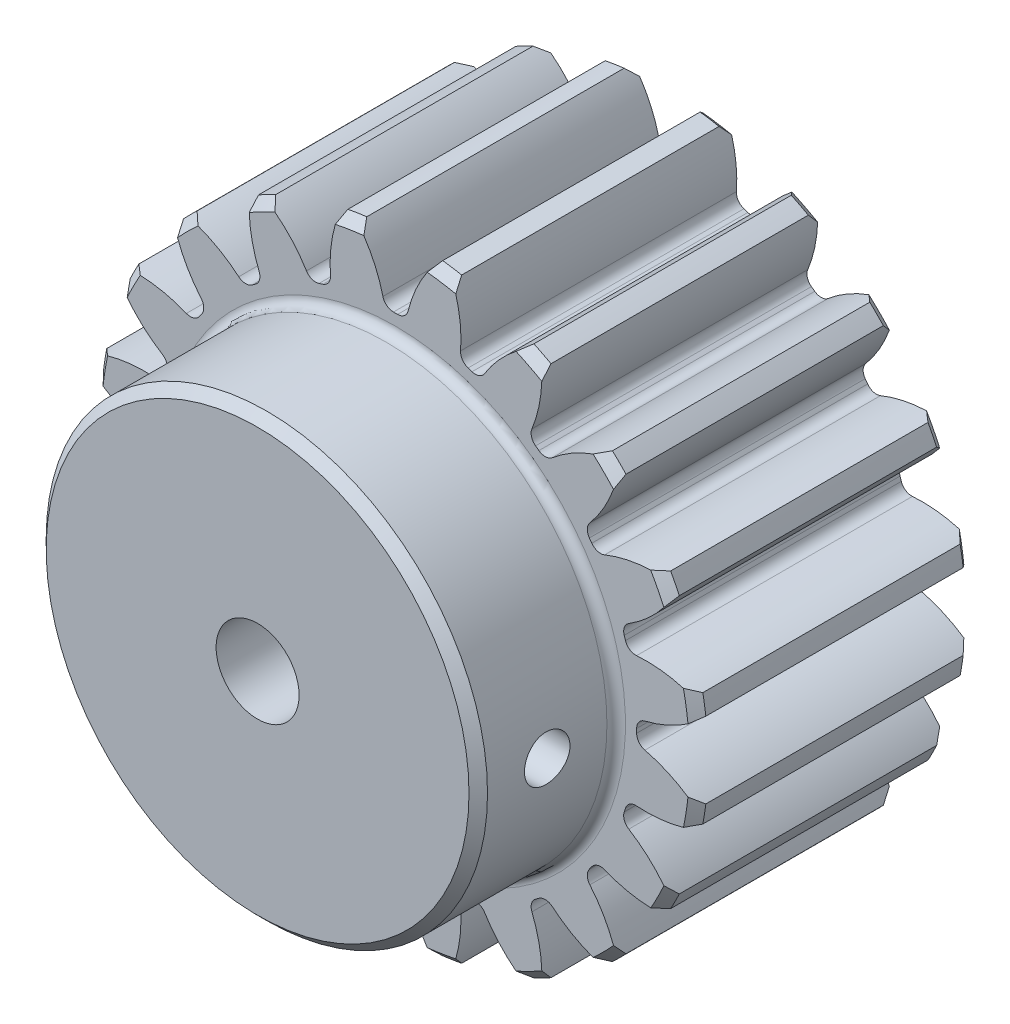
SolidWorks part; units mm, degrees
ref_plane "Front Plane" through (0, 0, 0) normal (0, 0, 1) x (1, 0, 0)
ref_plane "Top Plane" through (0, 0, 0) normal (0, 1, 0) x (1, 0, 0)
ref_plane "Right Plane" through (0, 0, 0) normal (1, 0, 0) x (0, 0, -1)
sketch "Sketch1" plane through (0, 0, 0) normal (0, 0, 1) x (1, 0, 0)
  line L0 (0, 0) -> (0, 20) construction
  line L1 (-6.4279, 22.3396) -> (6.4279, 17.6604) construction
  circle A0 centre (0, 0) radius 17.5 construction
  circle A1 centre (0, 0) radius 22 construction
  circle A2 centre (0, 0) radius 20 construction
  circle A3 centre (0, 0) radius 18.7939 construction
  circle A4 centre (0, 0) radius 16 construction
  circle A5 centre (0, 0) radius 6 construction
  point P8 (1, 0)
  point P13 (10, 0)
  dimension "OD" = 44
  dimension "Root Diameter" = 35
  dimension "Gear Pitch Diameter" = 40
  dimension "Base Diameter" = 37.5877
  dimension "Hub Diameter" = 32
  dimension "For Shaft Diameter" = 12
  dimension "Pressure Angle" = 20
  dimension "Number of Teeth" = 20
  dimension "Module" = 2
sketch "Sketch2" plane through (0, 0, 0) normal (1, 0, 0) x (0, 0, -1)
  line L0 (-10, 0) -> (20, 0) construction
  line L1 (20, 22) -> (20, -22) construction
  line L2 (0, -16) -> (-10, -16) construction
  line L3 (-10, 22) -> (20, 22) construction
  line L8 (-10, -16) -> (-10, 16) construction
  point P4 (0, 22)
  point P5 (-5, 0)
  dimension "Overall Width" = 30
  dimension "Hub Width" = 10
  dimension "Approx Set Screw Positon" = 5
  dimension "Face Width" = 20
sketch "Sketch3" plane through (0, 0, 0) normal (0, 0, 1) x (1, 0, 0)
  circle A0 centre (0, 0) radius 22
  circle A1 centre (0, 0) radius 22 construction
extrude "Boss-Extrude1" add sketch "Sketch3" against normal up to vertex (20 mm away) and the other way up to vertex (10 mm away) up to point (0, 0, -20) other way up to point (0, 0, 10)
sketch "Sketch5" plane through (0, 0, 0) normal (1, 0, 0) x (0, 0, -1)
  line L1 (0, 16) -> (-10, 16)
  line L2 (0, 16) -> (0, 22)
  line L3 (0, 22) -> (-10, 22)
  line L4 (-10, 16) -> (-10, 22)
  line L5 (-10, 0) -> (20, 0)
  line L6 (-10, 0) -> (-10, 6)
  line L7 (-10, 6) -> (20, 6)
  line L8 (20, 0) -> (20, 6)
  point P5 (0, 16)
  point P12 (0, 6)
revolve "Cut-Revolve1" cut sketch "Sketch5" angle 360 about L0
fillet "Fillet2" radius 0.671 1 edges at (0, -16, 0)
chamfer "Chamfer1" distance 0.671 angle 45 5 edges at (0, -6, -20) (0, -22, 0) (22, 0, -20) (0, -6, 10) (0, -16, 10)
sketch "Sketch4" plane through (0, 0, 0) normal (0, 0, 1) x (1, 0, 0)
  line L0 (17.4824, 0.7854) -> (17.4824, -0.7854)
  arc A3 (21.827, 2.7536) -> (21.827, -2.7536) centre (0, 0) cw
  circle A4 centre (0, 0) radius 22 construction
  arc A5 (17.4824, 0.7854) -> (21.827, 2.7536) centre (15.7482, 10.3925) ccw
  circle A8 centre (0, 0) radius 17.5 construction
  arc A9 (17.4824, -0.7854) -> (21.827, -2.7536) centre (15.7482, -10.3925) cw
  spline S0 degree 4 poles (18.7558, 1.1951) (18.7609, 1.1955) (18.7753, 1.1968) (18.8024, 1.2001) (18.8466, 1.2066) (18.9026, 1.2166) (18.9748, 1.2314) (19.0595, 1.2513) (19.1523, 1.2758) (19.2527, 1.3052) (19.3525, 1.337) (19.4517, 1.371) (19.55, 1.4069) (19.6686, 1.4528) (19.8101, 1.5113) (19.9744, 1.5844) (20.1594, 1.6731) (20.3463, 1.7697) (20.5289, 1.8696) (20.7118, 1.9763) (20.8875, 2.0836) (21.0683, 2.2008) (21.2342, 2.312) (21.4181, 2.4428) (21.5658, 2.5503) (21.7584, 2.6988) (21.8714, 2.7885) (22.0028, 2.8958) (22.0607, 2.9446) (22.0964, 2.9747) knots 0 0 0 0 0 0.005377 0.015084 0.028532 0.04661 0.064855 0.092111 0.119476 0.146842 0.174209 0.201575 0.228941 0.256307 0.307035 0.361767 0.4165 0.471232 0.525964 0.580697 0.635429 0.690161 0.744894 0.799626 0.854358 0.909091 0.954545 1 1 1 1 1 construction
  spline S1 degree 4 poles (18.7558, 1.1951) (18.7609, 1.1955) (18.7753, 1.1968) (18.8024, 1.2001) (18.8466, 1.2066) (18.9026, 1.2166) (18.9748, 1.2314) (19.0595, 1.2513) (19.1523, 1.2758) (19.2527, 1.3052) (19.3525, 1.337) (19.4517, 1.371) (19.55, 1.4069) (19.6686, 1.4528) (19.8101, 1.5113) (19.9744, 1.5844) (20.1594, 1.6731) (20.3463, 1.7697) (20.5289, 1.8696) (20.7118, 1.9763) (20.8875, 2.0836) (21.0683, 2.2008) (21.2342, 2.312) (21.4181, 2.4428) (21.5658, 2.5503) (21.7166, 2.6666) (21.7897, 2.724) (21.827, 2.7536) knots 0 0 0 0 0 0.005377 0.015084 0.028532 0.04661 0.064855 0.092111 0.119476 0.146842 0.174209 0.201575 0.228941 0.256307 0.307035 0.361767 0.4165 0.471232 0.525964 0.580697 0.635429 0.690161 0.744894 0.799626 0.854358 0.909091 0.909091 0.909091 0.909091 0.909091 construction
  spline S2 degree 4 poles (18.7558, -1.1951) (18.7609, -1.1955) (18.7753, -1.1968) (18.8024, -1.2001) (18.8466, -1.2066) (18.9026, -1.2166) (18.9748, -1.2314) (19.0595, -1.2513) (19.1523, -1.2758) (19.2527, -1.3052) (19.3525, -1.337) (19.4517, -1.371) (19.55, -1.4069) (19.6686, -1.4528) (19.8101, -1.5113) (19.9744, -1.5844) (20.1594, -1.6731) (20.3463, -1.7697) (20.5289, -1.8696) (20.7118, -1.9763) (20.8875, -2.0836) (21.0683, -2.2008) (21.2342, -2.312) (21.4181, -2.4428) (21.5658, -2.5503) (21.7584, -2.6988) (21.8714, -2.7885) (22.0028, -2.8958) (22.0607, -2.9446) (22.0964, -2.9747) knots 0 0 0 0 0 0.005377 0.015084 0.028532 0.04661 0.064855 0.092111 0.119476 0.146842 0.174209 0.201575 0.228941 0.256307 0.307035 0.361767 0.4165 0.471232 0.525964 0.580697 0.635429 0.690161 0.744894 0.799626 0.854358 0.909091 0.954545 1 1 1 1 1 construction
  spline S3 degree 4 poles (18.7558, -1.1951) (18.7609, -1.1955) (18.7753, -1.1968) (18.8024, -1.2001) (18.8466, -1.2066) (18.9026, -1.2166) (18.9748, -1.2314) (19.0595, -1.2513) (19.1523, -1.2758) (19.2527, -1.3052) (19.3525, -1.337) (19.4517, -1.371) (19.55, -1.4069) (19.6686, -1.4528) (19.8101, -1.5113) (19.9744, -1.5844) (20.1594, -1.6731) (20.3463, -1.7697) (20.5289, -1.8696) (20.7118, -1.9763) (20.8875, -2.0836) (21.0683, -2.2008) (21.2342, -2.312) (21.4181, -2.4428) (21.5658, -2.5503) (21.7166, -2.6666) (21.7897, -2.724) (21.827, -2.7536) knots 0 0 0 0 0 0.005377 0.015084 0.028532 0.04661 0.064855 0.092111 0.119476 0.146842 0.174209 0.201575 0.228941 0.256307 0.307035 0.361767 0.4165 0.471232 0.525964 0.580697 0.635429 0.690161 0.744894 0.799626 0.854358 0.909091 0.909091 0.909091 0.909091 0.909091 construction
  dimension "D1" = 1.5708
extrude "Cut-Extrude1" cut sketch "Sketch4" against normal through all both and the other way through all
fillet "Fillet1" radius 0.7854 2 edges at (17.4824, 0.7854, -10) (17.4824, -0.7854, -10)
pattern_circular "CirPattern1" count 20 over 360 about axis through (0, 0, 0) along (0, 0, 1) of "Cut-Extrude1", "Fillet1"
sketch "Sketch6" plane through (0, 0, 10) normal (0, 0, 1) x (1, 0, 0)
  circle A0 centre (0, 0) radius 6.671
  circle A1 centre (0, 0) radius 3.0075
  circle A2 centre (0, 0) radius 6.671 construction
  circle M2 centre (0, 0) radius 6.671
  dimension "D1" = 6.015
extrude "Boss-Extrude4" add sketch "Sketch6" against normal through all contours A1 M2
sketch "Sketch7" plane through (0, 0, 0) normal (1, 0, 0) x (0, 0, -1)
  line L0 (-10, 0) -> (0, 0) construction
  line L1 (-10, 15.329) -> (-10, -15.329) construction
  line L2 (0, 16.671) -> (0, -16.671) construction
  circle A0 centre (-5, 0) radius 2.8
  circle A1 centre (-5, 0) radius 2.25
  dimension "D1" = 5.6
  dimension "D2" = 4.5
sketch "Sketch8" plane through (0, 0, 0) normal (1, 0, 0) x (0, 0, -1)
  point P0 (-5, 0)
hole_wizard "M4x0.7 Tapped Hole1" positions "Sketch8" profile "Sketch9" tap size "M4x0.7" standard "ANSI Metric"
sketch "Sketch9" plane through (0, 0, 5) normal (0, 1, 0) x (0, 0, 1)
  line L0 (0, 0) -> (0, 21.827)
  line L1 (0, 21.827) -> (1.65, 21.827)
  line L2 (1.65, 21.827) -> (1.65, 0)
  line L5 (1.65, 0) -> (0, 0)
  line L11 (0, -6.35) -> (0, 107.95) construction
  dimension "Thru Tap Drill Dia." = 3.3
  dimension "Thru Tap Drill Depth" = 21.827
cosmetic thread "Hole Thread1" parameters "D2"=4
equation "\"Number of Teeth\"= 20"
equation "\"Module\"= 2"
equation "\"Diametral Pitch\"= 1 / \"Module\""
equation "\"Dedendum\"= 1.25 / \"Diametral Pitch\""
equation "\"Pitch Diameter\"= \"Module\" * \"Number of Teeth\""
equation "\"Root Diameter\"= \"Pitch Diameter\" - ( 2 * \"Dedendum\" )"
equation "\"Root Diameter@Sketch1\"=\"Root Diameter\""
equation "\"OD@Sketch1\" = \"Outside Diameter\""
equation "\"D1@CirPattern1\"=\"Number of Teeth\""
equation "\"Pressure Angle\"=20"
equation "\"Base Diameter\"= \"Pitch Diameter\" * cos ( \"Pressure Angle\" )"
equation "\"Outside Diameter\"= ( \"Number of Teeth\" + 2 ) / \"Diametral Pitch\""
equation "\"Pitch Angle\"= 360deg / \"Number of Teeth\""
equation "\"Alpha\"= sqr ( \"Pitch Diameter\" ^ 2 - \"Base Diameter\" ^ 2 ) / \"Base Diameter\" * 180 / PI - \"Pressure Angle\""
equation "\"Beta\"= ( \"Pitch Angle\" / 4 - \"Alpha\" )"
equation "\"Phi\"= sqr ( ( \"Outside Diameter\" / 2 ) ^ 2 - ( \"Base Diameter\" / 2 ) ^ 2 ) / ( \"Base Diameter\" / 2 )"
equation "\"Addendum\"= 1 / \"Diametral Pitch\""
equation "\"WorkingDepth\"= 2 / \"Diametral Pitch\""
equation "\"WholeDepth\"= 2.25 / \"Diametral Pitch\""
equation "\"Clearance\"= 0.25 / \"Diametral Pitch\""
equation "\"ToothThickness\"= ( pi * 2 ) / \"Diametral Pitch\""
equation "\"CircularPitch\"= pi / \"Diametral Pitch\""
equation "\"Number of Teeth@Sketch1\"=\"Number of Teeth\""
equation "\"Module@Sketch1\"=\"Module\""
equation "\"Pressure Angle@Sketch1\"=\"Pressure Angle\""
equation "\"Gear Pitch Diameter@Sketch1\"=\"Pitch Diameter\""
equation "\"Base Diameter@Sketch1\"=\"Base Diameter\""
equation "\"Fillet\"= \"Clearance\" * cos ( \"Pressure Angle\" ) * tan ( ( 90 + \"Pressure Angle\" ) / 2 )"
equation "\"D1@Fillet2\"=\"Fillet\""
equation "\"Approx Set Screw Positon@Sketch2\" = \"Hub Width@Sketch2\" / 2"
equation "\"D2\"= \"Fillet\" * 2"
equation "\"D1@Chamfer1\"=\"Fillet\""
equation "\"D1@Sketch4\"=\"CircularPitch\"*0.25"
equation "\"D1@Fillet1\"=\"CircularPitch\"*0.125"
